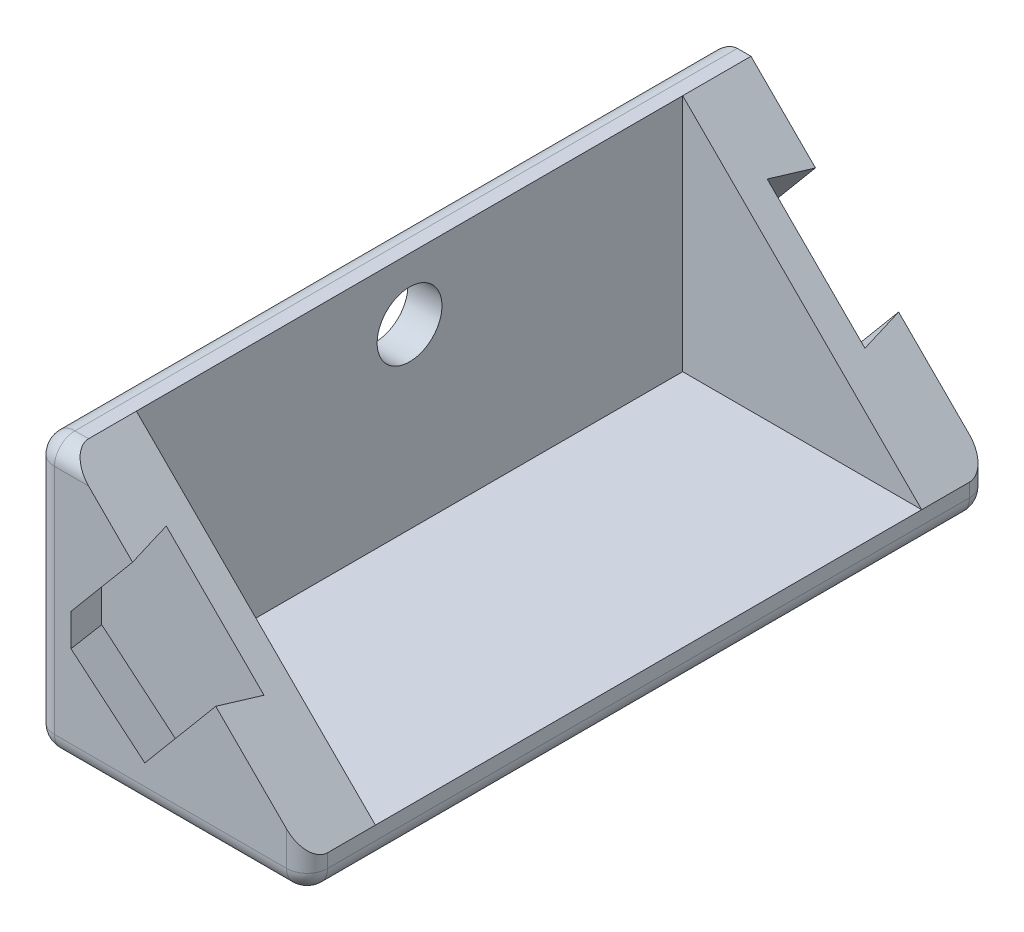
SolidWorks part; units mm, degrees
ref_plane "前视基准面" through (0, 0, 0) normal (0, 0, 1) x (1, 0, 0)
ref_plane "上视基准面" through (0, 0, 0) normal (0, 1, 0) x (1, 0, 0)
ref_plane "右视基准面" through (0, 0, 0) normal (1, 0, 0) x (0, 0, -1)
sketch "草图1" plane through (0, 0, 0) normal (0, 0, 1) x (1, 0, 0)
  line L0 (0, 0) -> (-100, -119.1754)
  line L1 (-100, -119.1754) -> (-55, -119.1754)
  line L2 (100, -119.1754) -> (0, 0)
  line L3 (-100, -119.1754) -> (-100, -74.1754)
  line L4 (-100, -74.1754) -> (-55, -119.1754)
  line L6 (0, 0) -> (0, 50000) construction
  line L7 (0, 15.5572) -> (-96, -98.8511)
  line L8 (-10.5203, -28.0949) -> (-83.5895, -115.1754)
  line L9 (7.6604, -6.4279) -> (-92.3396, -125.6032) construction
  line L10 (-7.6604, 6.4279) -> (-107.6604, -112.7475) construction
  line L13 (0, 0) -> (-42.5357, 0) construction
  line L14 (0, -119.1754) -> (100, -119.1754)
  line L21 (-96, -104.7617) -> (-83.5895, -115.1754)
  line L22 (-96, -119.1754) -> (-96, -88.5856) construction
  line L23 (-96, -98.8511) -> (-96, -104.7617)
  line L24 (1.1491, 14.5931) -> (-94.5, -99.3971)
  line L25 (-94.5, -99.3971) -> (-94.5, -104.0623)
  line L26 (-94.5, -104.0623) -> (-83.7744, -113.0621)
  line L27 (-11.6694, -27.1307) -> (-83.7744, -113.0621)
  line L28 (-81.6478, -81.7469) -> (-66.327, -94.6026)
  circle A0 centre (0, 0) radius 4
  circle A1 centre (0, 0) radius 11.15
  circle A2 centre (0, 0) radius 30
  dimension "D4" = 8
  dimension "D11" = 22.3
  dimension "D12" = 60
  dimension "D1" = 200
  dimension "D2" = 50
  dimension "D3" = 45
  dimension "D7" = 45
  dimension "D8" = 4
  dimension "D9" = 4
  dimension "D10" = 1.5
  dimension "D5" = 10
  dimension "D6" = 10
sketch "草图3" plane through (0, 0, 0) normal (0, 0, 1) x (1, 0, 0)
  line L0 (-100, -119.1754) -> (-55, -119.1754) construction
  line L1 (-100, -74.1754) -> (-55, -119.1754) construction
  line L2 (-100, -119.1754) -> (-100, -74.1754) construction
  line L3 (-100, -119.1754) -> (-55, -119.1754)
  line L4 (-100, -74.1754) -> (-55, -119.1754)
  line L5 (-100, -119.1754) -> (-100, -74.1754)
  line L6 (-100, -79.1754) -> (-95, -79.1754)
  line L7 (-60, -114.1754) -> (-60, -119.1754)
  dimension "D1" = 5
  dimension "D2" = 5
extrude "凸台-拉伸1" add sketch "草图3" against normal blind 10 contours L7 L4 L6 L5 L3
sketch "草图8" plane through (0, 0, 0) normal (0, 0, 1) x (1, 0, 0)
  line L46 (-81.6478, -81.7469) -> (-66.327, -94.6026) construction
  line L47 (-80.5601, -82.6596) -> (-67.4147, -93.6899)
  line L50 (-94.58, -99.3679) -> (1.0878, 14.6445)
  line L56 (-11.6081, -27.1821) -> (-83.7646, -113.1748)
  line L57 (-83.7646, -113.1748) -> (-94.58, -104.0996)
  line L58 (-94.58, -104.0996) -> (-94.58, -99.3679)
  line L59 (-94.58, -99.3679) -> (-80.5601, -82.6596)
  line L60 (-67.4147, -93.6899) -> (-83.7646, -113.1748)
  line L61 (-83.7646, -113.1748) -> (-94.58, -104.0996)
  line L62 (-94.58, -104.0996) -> (-94.58, -99.3679)
  dimension "D1" = 0.08
ref_plane "基准面1" through (0, 0, -6) normal (0, 0, 1) x (1, 0, 0)
sketch "草图5" plane through (0, 0, -6) normal (0, 0, 1) x (1, 0, 0)
  line L19 (-1.5366, 10.948) -> (0.8296, 14.9915)
  line L41 (-1.9367, 19.372) -> (0.4289, -30.4396)
  line L42 (-1.5366, 10.948) -> (0.8296, 14.9915)
  line L69 (-81.6478, -81.7469) -> (-66.327, -94.6026) construction
  line L70 (-81.7091, -81.6955) -> (-66.2657, -94.6541)
  line L71 (-1.6671, 13.6949) -> (-0.0613, 15.6087)
  line L73 (-96.08, -98.822) -> (-0.0613, 15.6087)
  line L74 (-10.4591, -28.1463) -> (-83.5797, -115.2881)
  line L75 (-83.5797, -115.2881) -> (-96.08, -104.799)
  line L76 (-96.08, -104.799) -> (-96.08, -98.822)
  line L77 (-96.08, -98.822) -> (-81.7091, -81.6955)
  line L78 (-66.2657, -94.6541) -> (-83.5797, -115.2881)
  line L79 (-83.5797, -115.2881) -> (-96.08, -104.799)
  line L80 (-96.08, -104.799) -> (-96.08, -98.822)
  dimension "D1" = 0.08
loft "切除-放样1" cut section "草图5" section "草图8"
sketch "草图9" plane through (0, 0, -10) normal (0, 0, -1) x (-1, 0, 0)
  line L0 (100, -119.1754) -> (55, -119.1754) construction
  line L1 (100, -119.1754) -> (100, -74.1754) construction
  line L2 (100, -119.1754) -> (60, -119.1754)
  line L3 (100, -119.1754) -> (100, -79.1754)
  line L4 (95, -79.1754) -> (95, -114.1754)
  line L5 (60, -114.1754) -> (60, -119.1754)
  line L6 (60, -119.1754) -> (100, -119.1754)
  line L7 (100, -119.1754) -> (100, -79.1754)
  line L8 (100, -79.1754) -> (95, -79.1754)
  line L9 (95, -79.1754) -> (60, -114.1754)
  line L10 (60, -114.1754) -> (60, -119.1754)
  line L11 (60, -119.1754) -> (100, -119.1754)
  line L12 (100, -119.1754) -> (100, -79.1754)
  line L13 (100, -79.1754) -> (95, -79.1754)
  line L15 (95, -114.1754) -> (60, -114.1754)
  line M7 (60, -114.1754) -> (60, -119.1754)
  line M8 (60, -119.1754) -> (100, -119.1754)
  line M9 (100, -119.1754) -> (100, -79.1754)
  line M10 (100, -79.1754) -> (95, -79.1754)
  dimension "D1" = 0
extrude "凸台-拉伸3" add sketch "草图9" along normal blind 40 contours L4 L15 M7 M8 M9 M10
mirror "镜向2" about plane through (0, 0, -50) normal (0, 0, -1) of bodies 112
fillet "圆角2" radius 3 6 edges at (-60, -116.6754, -100) (-60, -116.6754, 0) (-100, -99.1754, -100) (-100, -99.1754, 0) (-100, -79.1754, -50) (-97.5, -79.1754, 0)
fillet "圆角3" radius 3 8 edges at (-99.1213, -119.1754, -0.8787) (-100, -119.1754, -50) (-99.1213, -119.1754, -99.1213) (-80, -119.1754, -100) (-60.8787, -119.1754, -99.1213) (-60, -119.1754, -50) (-60.8787, -119.1754, -0.8787) (-80, -119.1754, 0)
sketch "草图10" plane through (-100, 0, 0) normal (-1, 0, 0) x (0, 0, 1)
  line L0 (-51.5, -79.1754) -> (-51.5, -119.1754) construction
  line L1 (-100, -79.1754) -> (-3, -79.1754) construction
  line L2 (-3, -119.1754) -> (-97, -119.1754) construction
  line L3 (-90, -114.1754) -> (-10, -114.1754) construction
  line L5 (-29.85, -114.1754) -> (-29.85, -79.1754)
  line L7 (-73.15, -114.1754) -> (-73.15, -79.1754)
  line L8 (-51.5, -79.1754) -> (-51.5, -119.1754) construction
  line L9 (-29.85, -96.6754) -> (-73.15, -96.6754) construction
  line L10 (-73.15, -114.1754) -> (-29.85, -114.1754)
  line L11 (-73.15, -79.1754) -> (-29.85, -79.1754)
  point P6 (-51.5, -96.6754)
  dimension "D2" = 43.3
extrude "切除-拉伸1" [suppressed] cut sketch "草图10" against normal blind 12.8
sketch "草图11" [suppressed] plane through (0, -114.1754, 0) normal (0, 1, 0) x (1, 0, 0)
  line L0 (-83, 25.85) -> (-95, 25.85)
  line L1 (-60, 50) -> (-50060, 50) construction
  line L2 (-60, 90) -> (-60, 10) construction
  line L4 (-83, 77.15) -> (-83, 25.85)
  line L9 (-95, 29.85) -> (-95, 10) construction
  line L13 (-83, 77.15) -> (-95, 77.15)
  line L14 (-95, 90) -> (-95, 73.15) construction
  line L15 (-95, 77.15) -> (-95, 73.15)
  line L16 (-95, 29.85) -> (-95, 25.85)
  line L18 (-95, 73.15) -> (-87, 73.15)
  line L19 (-87, 73.15) -> (-87, 29.85)
  line L20 (-87, 29.85) -> (-95, 29.85)
  line L21 (-100, 73.15) -> (-100, 29.85) construction
  point P4 (-60, 50)
  dimension "D1" = 4
  dimension "D2" = 13
  dimension "D3" = 4
  dimension "D4" = 4
extrude "凸台-拉伸4" [suppressed] add sketch "草图11" along normal up to surface (35 mm away)
sketch "草图12" [suppressed] plane through (0, -79.1754, 0) normal (0, 1, 0) x (1, 0, 0)
  line L0 (-95, 77.15) -> (-83, 77.15) construction
  line L1 (-83, 25.85) -> (-100, 25.85)
  line L2 (-83, 25.85) -> (-83, 77.15)
  line L3 (-83, 77.15) -> (-100, 77.15)
  line L4 (-100, 25.85) -> (-100, 77.15)
  line L5 (-91.5, 77.15) -> (-91.5, 25.85) construction
  line L6 (-83, 51.5) -> (-100, 51.5) construction
  line L7 (-95, 25.85) -> (-83, 25.85) construction
  line L8 (-83, 77.15) -> (-83, 25.85) construction
  line L9 (-100, 73.15) -> (-100, 29.85) construction
  line L11 (-49.5567, -0.9458) -> (-111.1305, -0.9458)
  line L12 (-49.5567, -0.9458) -> (-49.5567, 103.9458)
  line L13 (-49.5567, 103.9458) -> (-111.1305, 103.9458)
  line L14 (-111.1305, -0.9458) -> (-111.1305, 103.9458)
  line L15 (-80.3436, 103.9458) -> (-80.3436, -0.9458) construction
  line L16 (-49.5567, 51.5) -> (-111.1305, 51.5) construction
  point P0 (-91.5, 51.5)
  point P15 (-80.3436, 51.5)
extrude "切除-拉伸2" [suppressed] cut sketch "草图12" against normal through all
sketch "草图13" plane through (-100, 0, 0) normal (-1, 0, 0) x (0, 0, 1)
  line L0 (-3, -82.1754) -> (-97, -82.1754) construction
  circle A0 centre (-50, -88.1754) radius 4.75
  dimension "D1" = 6
extrude "切除-拉伸3" cut sketch "草图13" against normal blind 10
ref_plane "基准面2" through (0, 0, -10) normal (0, 0, -1) x (-1, 0, 0)
other "使用曲面切除1"
